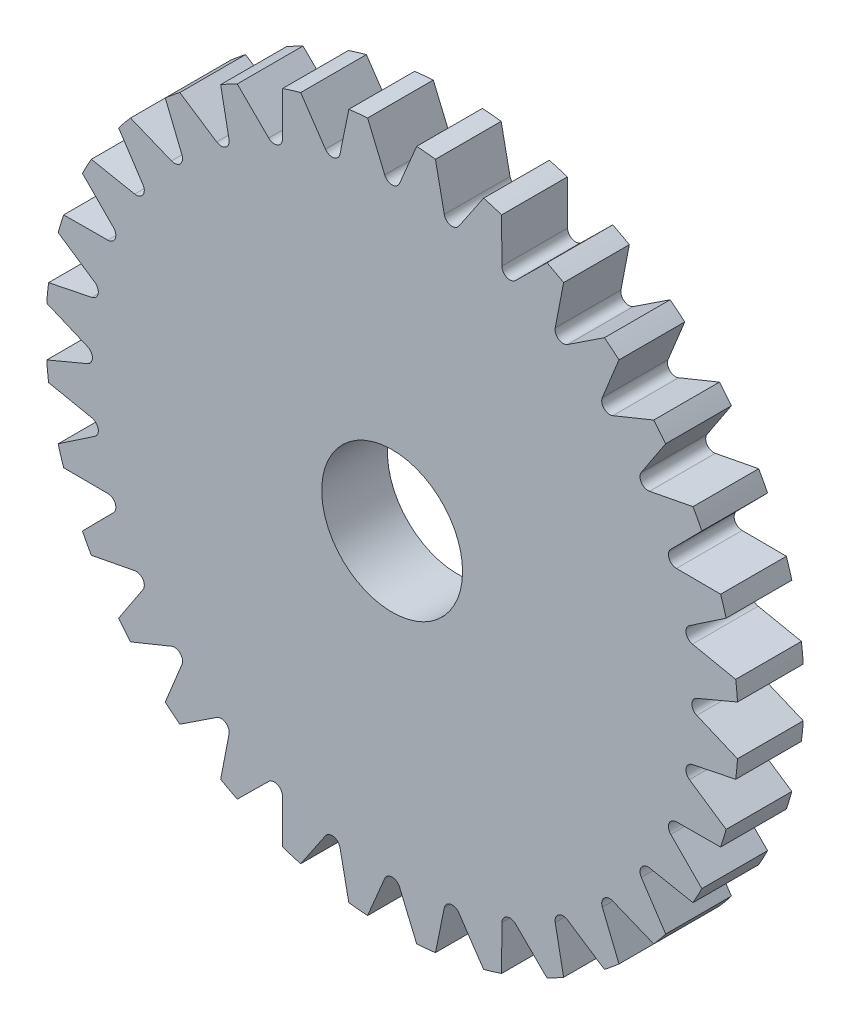
SolidWorks part; units mm, degrees
ref_plane "Front Plane" through (0, 0, 0) normal (0, 0, 1) x (1, 0, 0)
ref_plane "Top Plane" through (0, 0, 0) normal (0, 1, 0) x (1, 0, 0)
ref_plane "Right Plane" through (0, 0, 0) normal (1, 0, 0) x (0, 0, -1)
sketch "Sketch1" plane through (0, 0, 0) normal (0, 0, 1) x (1, 0, 0)
  circle A80 centre (0, 0) radius 16.8606
  circle A82 centre (0, 0) radius 3.429
  dimension "D9" = 33.7212
  dimension "D1" = 6.858
extrude "Boss-Extrude1" add sketch "Sketch1" along normal mid plane 3.2004
sketch "Sketch2" plane through (0, 0, 1.6002) normal (0, 0, 1) x (1, 0, 0)
  line L0 (0, 16.8181) -> (0, 0) construction
  line L1 (1.557, 31.6527) -> (0, 0) construction
  line L2 (-1.1958, 16.8181) -> (1.1958, 16.8181) construction
  line L3 (-0.7785, 15.8263) -> (0.7785, 15.8263) construction
  line L4 (-1.1958, 16.8181) -> (-0.3613, 14.8345)
  line L5 (1.1958, 16.8181) -> (0.3613, 14.8345)
  line L6 (4.4538, 16.2617) -> (3.2484, 14.479)
  line L7 (2.1083, 16.7283) -> (2.5398, 14.62)
  line L8 (7.5408, 15.0803) -> (6.0107, 13.5671)
  line L9 (5.3313, 15.9955) -> (5.3432, 13.8436)
  line L10 (10.3379, 13.3195) -> (8.542, 12.1338)
  line L11 (8.3494, 14.6481) -> (7.9413, 12.5352)
  line L12 (12.7378, 11.0467) -> (10.7451, 10.2342)
  line L13 (11.0467, 12.7378) -> (10.2342, 10.7451)
  line L14 (14.6481, 8.3494) -> (12.5352, 7.9413)
  line L15 (13.3195, 10.3379) -> (12.1338, 8.542)
  line L16 (15.9955, 5.3313) -> (13.8436, 5.3432)
  line L17 (15.0803, 7.5408) -> (13.5671, 6.0107)
  line L18 (16.7283, 2.1083) -> (14.62, 2.5398)
  line L19 (16.2617, 4.4538) -> (14.479, 3.2484)
  line L20 (16.8181, -1.1958) -> (14.8345, -0.3613)
  line L21 (16.8181, 1.1958) -> (14.8345, 0.3613)
  line L22 (16.2617, -4.4538) -> (14.479, -3.2484)
  line L23 (16.7283, -2.1083) -> (14.62, -2.5398)
  line L24 (15.0803, -7.5408) -> (13.5671, -6.0107)
  line L25 (15.9955, -5.3313) -> (13.8436, -5.3432)
  line L26 (13.3195, -10.3379) -> (12.1338, -8.542)
  line L27 (14.6481, -8.3494) -> (12.5352, -7.9413)
  line L28 (11.0467, -12.7378) -> (10.2342, -10.7451)
  line L29 (12.7378, -11.0467) -> (10.7451, -10.2342)
  line L30 (8.3494, -14.6481) -> (7.9413, -12.5352)
  line L31 (10.3379, -13.3195) -> (8.542, -12.1338)
  line L32 (5.3313, -15.9955) -> (5.3432, -13.8436)
  line L33 (7.5408, -15.0803) -> (6.0107, -13.5671)
  line L34 (2.1083, -16.7283) -> (2.5398, -14.62)
  line L35 (4.4538, -16.2617) -> (3.2484, -14.479)
  line L36 (-1.1958, -16.8181) -> (-0.3613, -14.8345)
  line L37 (1.1958, -16.8181) -> (0.3613, -14.8345)
  line L38 (-4.4538, -16.2617) -> (-3.2484, -14.479)
  line L39 (-2.1083, -16.7283) -> (-2.5398, -14.62)
  line L40 (-7.5408, -15.0803) -> (-6.0107, -13.5671)
  line L41 (-5.3313, -15.9955) -> (-5.3432, -13.8436)
  line L42 (-10.3379, -13.3195) -> (-8.542, -12.1338)
  line L43 (-8.3494, -14.6481) -> (-7.9413, -12.5352)
  line L44 (-12.7378, -11.0467) -> (-10.7451, -10.2342)
  line L45 (-11.0467, -12.7378) -> (-10.2342, -10.7451)
  line L46 (-14.6481, -8.3494) -> (-12.5352, -7.9413)
  line L47 (-13.3195, -10.3379) -> (-12.1338, -8.542)
  line L48 (-15.9955, -5.3313) -> (-13.8436, -5.3432)
  line L49 (-15.0803, -7.5408) -> (-13.5671, -6.0107)
  line L50 (-16.7283, -2.1083) -> (-14.62, -2.5398)
  line L51 (-16.2617, -4.4538) -> (-14.479, -3.2484)
  line L52 (-16.8181, 1.1958) -> (-14.8345, 0.3613)
  line L53 (-16.8181, -1.1958) -> (-14.8345, -0.3613)
  line L54 (-16.2617, 4.4538) -> (-14.479, 3.2484)
  line L55 (-16.7283, 2.1083) -> (-14.62, 2.5398)
  line L56 (-15.0803, 7.5408) -> (-13.5671, 6.0107)
  line L57 (-15.9955, 5.3313) -> (-13.8436, 5.3432)
  line L58 (-13.3195, 10.3379) -> (-12.1338, 8.542)
  line L59 (-14.6481, 8.3494) -> (-12.5352, 7.9413)
  line L60 (-11.0467, 12.7378) -> (-10.2342, 10.7451)
  line L61 (-12.7378, 11.0467) -> (-10.7451, 10.2342)
  line L62 (-8.3494, 14.6481) -> (-7.9413, 12.5352)
  line L63 (-10.3379, 13.3195) -> (-8.542, 12.1338)
  line L64 (-5.3313, 15.9955) -> (-5.3432, 13.8436)
  line L65 (-7.5408, 15.0803) -> (-6.0107, 13.5671)
  line L66 (-2.1083, 16.7283) -> (-2.5398, 14.62)
  line L67 (-4.4538, 16.2617) -> (-3.2484, 14.479)
  circle A0 centre (0, 0) radius 16.8606 construction
  arc A1 (-0.3613, 14.8345) -> (0.3613, 14.8345) centre (0, 14.9865) ccw
  arc A2 (-1.1958, 16.8181) -> (1.1958, 16.8181) centre (0, 0) cw
  arc A3 (2.1083, 16.7283) -> (4.4538, 16.2617) centre (0, 0) cw
  arc A4 (2.5398, 14.62) -> (3.2484, 14.479) centre (2.9237, 14.6986) ccw
  arc A5 (5.3313, 15.9955) -> (7.5408, 15.0803) centre (0, 0) cw
  arc A6 (5.3432, 13.8436) -> (6.0107, 13.5671) centre (5.7351, 13.8457) ccw
  arc A7 (8.3494, 14.6481) -> (10.3379, 13.3195) centre (0, 0) cw
  arc A8 (7.9413, 12.5352) -> (8.542, 12.1338) centre (8.3261, 12.4608) ccw
  arc A9 (11.0467, 12.7378) -> (12.7378, 11.0467) centre (0, 0) cw
  arc A10 (10.2342, 10.7451) -> (10.7451, 10.2342) centre (10.5971, 10.5971) ccw
  arc A11 (13.3195, 10.3379) -> (14.6481, 8.3494) centre (0, 0) cw
  arc A12 (12.1338, 8.542) -> (12.5352, 7.9413) centre (12.4608, 8.3261) ccw
  arc A13 (15.0803, 7.5408) -> (15.9955, 5.3313) centre (0, 0) cw
  arc A14 (13.5671, 6.0107) -> (13.8436, 5.3432) centre (13.8457, 5.7351) ccw
  arc A15 (16.2617, 4.4538) -> (16.7283, 2.1083) centre (0, 0) cw
  arc A16 (14.479, 3.2484) -> (14.62, 2.5398) centre (14.6986, 2.9237) ccw
  arc A17 (16.8181, 1.1958) -> (16.8181, -1.1958) centre (0, 0) cw
  arc A18 (14.8345, 0.3613) -> (14.8345, -0.3613) centre (14.9865, 0) ccw
  arc A19 (16.7283, -2.1083) -> (16.2617, -4.4538) centre (0, 0) cw
  arc A20 (14.62, -2.5398) -> (14.479, -3.2484) centre (14.6986, -2.9237) ccw
  arc A21 (15.9955, -5.3313) -> (15.0803, -7.5408) centre (0, 0) cw
  arc A22 (13.8436, -5.3432) -> (13.5671, -6.0107) centre (13.8457, -5.7351) ccw
  arc A23 (14.6481, -8.3494) -> (13.3195, -10.3379) centre (0, 0) cw
  arc A24 (12.5352, -7.9413) -> (12.1338, -8.542) centre (12.4608, -8.3261) ccw
  arc A25 (12.7378, -11.0467) -> (11.0467, -12.7378) centre (0, 0) cw
  arc A26 (10.7451, -10.2342) -> (10.2342, -10.7451) centre (10.5971, -10.5971) ccw
  arc A27 (10.3379, -13.3195) -> (8.3494, -14.6481) centre (0, 0) cw
  arc A28 (8.542, -12.1338) -> (7.9413, -12.5352) centre (8.3261, -12.4608) ccw
  arc A29 (7.5408, -15.0803) -> (5.3313, -15.9955) centre (0, 0) cw
  arc A30 (6.0107, -13.5671) -> (5.3432, -13.8436) centre (5.7351, -13.8457) ccw
  arc A31 (4.4538, -16.2617) -> (2.1083, -16.7283) centre (0, 0) cw
  arc A32 (3.2484, -14.479) -> (2.5398, -14.62) centre (2.9237, -14.6986) ccw
  arc A33 (1.1958, -16.8181) -> (-1.1958, -16.8181) centre (0, 0) cw
  arc A34 (0.3613, -14.8345) -> (-0.3613, -14.8345) centre (0, -14.9865) ccw
  arc A35 (-2.1083, -16.7283) -> (-4.4538, -16.2617) centre (0, 0) cw
  arc A36 (-2.5398, -14.62) -> (-3.2484, -14.479) centre (-2.9237, -14.6986) ccw
  arc A37 (-5.3313, -15.9955) -> (-7.5408, -15.0803) centre (0, 0) cw
  arc A38 (-5.3432, -13.8436) -> (-6.0107, -13.5671) centre (-5.7351, -13.8457) ccw
  arc A39 (-8.3494, -14.6481) -> (-10.3379, -13.3195) centre (0, 0) cw
  arc A40 (-7.9413, -12.5352) -> (-8.542, -12.1338) centre (-8.3261, -12.4608) ccw
  arc A41 (-11.0467, -12.7378) -> (-12.7378, -11.0467) centre (0, 0) cw
  arc A42 (-10.2342, -10.7451) -> (-10.7451, -10.2342) centre (-10.5971, -10.5971) ccw
  arc A43 (-13.3195, -10.3379) -> (-14.6481, -8.3494) centre (0, 0) cw
  arc A44 (-12.1338, -8.542) -> (-12.5352, -7.9413) centre (-12.4608, -8.3261) ccw
  arc A45 (-15.0803, -7.5408) -> (-15.9955, -5.3313) centre (0, 0) cw
  arc A46 (-13.5671, -6.0107) -> (-13.8436, -5.3432) centre (-13.8457, -5.7351) ccw
  arc A47 (-16.2617, -4.4538) -> (-16.7283, -2.1083) centre (0, 0) cw
  arc A48 (-14.479, -3.2484) -> (-14.62, -2.5398) centre (-14.6986, -2.9237) ccw
  arc A49 (-16.8181, -1.1958) -> (-16.8181, 1.1958) centre (0, 0) cw
  arc A50 (-14.8345, -0.3613) -> (-14.8345, 0.3613) centre (-14.9865, 0) ccw
  arc A51 (-16.7283, 2.1083) -> (-16.2617, 4.4538) centre (0, 0) cw
  arc A52 (-14.62, 2.5398) -> (-14.479, 3.2484) centre (-14.6986, 2.9237) ccw
  arc A53 (-15.9955, 5.3313) -> (-15.0803, 7.5408) centre (0, 0) cw
  arc A54 (-13.8436, 5.3432) -> (-13.5671, 6.0107) centre (-13.8457, 5.7351) ccw
  arc A55 (-14.6481, 8.3494) -> (-13.3195, 10.3379) centre (0, 0) cw
  arc A56 (-12.5352, 7.9413) -> (-12.1338, 8.542) centre (-12.4608, 8.3261) ccw
  arc A57 (-12.7378, 11.0467) -> (-11.0467, 12.7378) centre (0, 0) cw
  arc A58 (-10.7451, 10.2342) -> (-10.2342, 10.7451) centre (-10.5971, 10.5971) ccw
  arc A59 (-10.3379, 13.3195) -> (-8.3494, 14.6481) centre (0, 0) cw
  arc A60 (-8.542, 12.1338) -> (-7.9413, 12.5352) centre (-8.3261, 12.4608) ccw
  arc A61 (-7.5408, 15.0803) -> (-5.3313, 15.9955) centre (0, 0) cw
  arc A62 (-6.0107, 13.5671) -> (-5.3432, 13.8436) centre (-5.7351, 13.8457) ccw
  arc A63 (-4.4538, 16.2617) -> (-2.1083, 16.7283) centre (0, 0) cw
  arc A64 (-3.2484, 14.479) -> (-2.5398, 14.62) centre (-2.9237, 14.6986) ccw
  point P9 (0, 15.8263)
  point P171 (0, 0)
  dimension "D1" = 0.9918
  dimension "D2" = 1.557
  dimension "D3" = 20
  dimension "D4" = 32
extrude "Cut-Extrude1" cut sketch "Sketch2" against normal up to surface (3.2004 mm away) up to face at (16.8606, 0, -1.6002)
sketch "Sketch3" plane through (0, 0, 1.6002) normal (0, 0, 1) x (1, 0, 0)
  circle A0 centre (0, 0) radius 15.8688 construction
  circle A1 centre (0, 0) radius 16.8606 construction
  dimension "D1" = 31.7376
